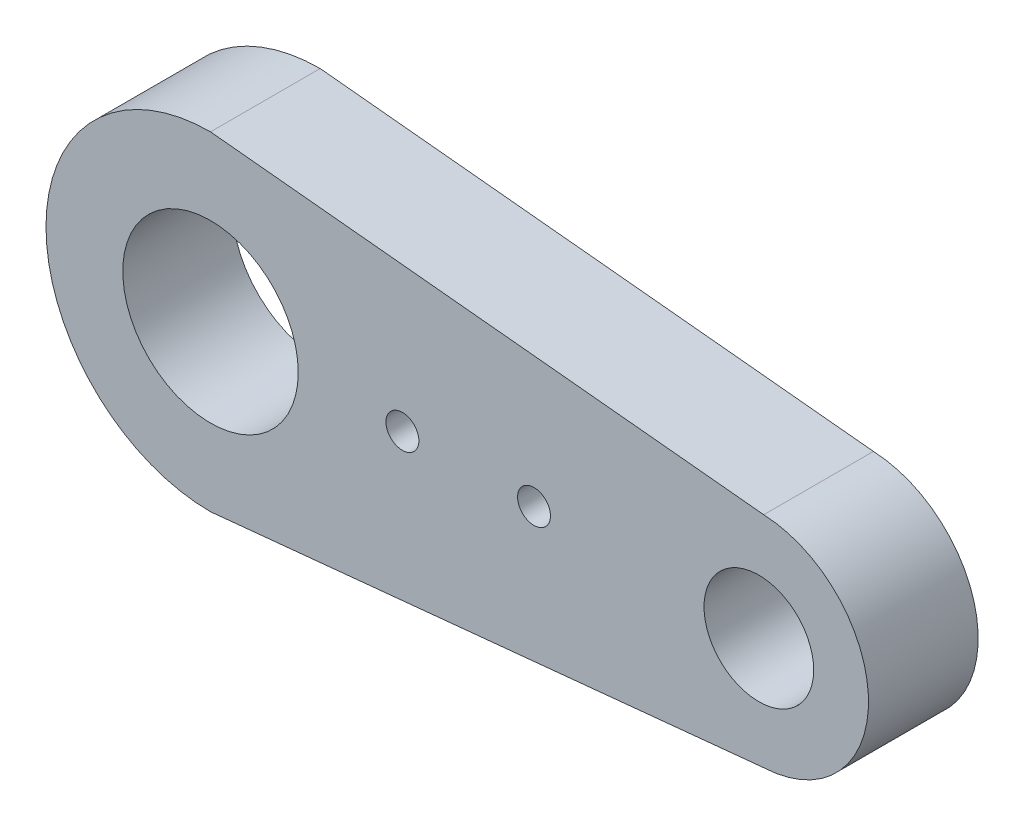
SolidWorks part; units mm, degrees
ref_plane "Front Plane" through (0, 0, 0) normal (0, 0, 1) x (1, 0, 0)
ref_plane "Top Plane" through (0, 0, 0) normal (0, 1, 0) x (1, 0, 0)
ref_plane "Right Plane" through (0, 0, 0) normal (1, 0, 0) x (0, 0, -1)
sketch "Sketch1" plane through (0, 0, 0) normal (0, 0, 1) x (1, 0, 0)
  line L3 (0, -1000) -> (0, -6.9359) construction
  line L8 (-12.5, 6.8227) -> (12.7234, 4.3177)
  line L9 (-1012.5, -0.6773) -> (-20, -0.6773) construction
  line L11 (-12.5, -8.1773) -> (12.7234, -5.6723)
  line L12 (17.5, -0.6773) -> (48987.5, -0.6773) construction
  line L13 (0, 5.5813) -> (0, 49000) construction
  arc A0 (12.7234, -5.6723) -> (12.7234, 4.3177) centre (12.5, -0.6773) ccw
  arc A1 (-12.5, 6.8227) -> (-12.5, -8.1773) centre (-12.5, -0.6773) ccw
  circle A2 centre (-12.5, -0.6773) radius 4
  circle A3 centre (12.5, -0.6773) radius 2.5
  arc A4 (16.8146, 1.8494) -> (8.1854, -3.204) centre (12.5, -0.6773) ccw construction
  circle A5 centre (12.5, -0.6773) radius 2.5 construction
  circle A6 centre (-12.5, -0.6773) radius 4 construction
  dimension "D3" = 25
  dimension "D1" = 15
extrude "Boss-Extrude1" add sketch "Sketch1" along normal blind 5
sketch "Sketch2" plane through (0, 0, 5) normal (0, 0, 1) x (1, 0, 0)
  circle A0 centre (-3.7501, -0.6279) radius 0.75
  circle A1 centre (2.2498, -0.5941) radius 0.75
  dimension "D1" = 1.5
  dimension "D2" = 1.5
extrude "Cut-Extrude1" cut sketch "Sketch2" against normal blind 10
